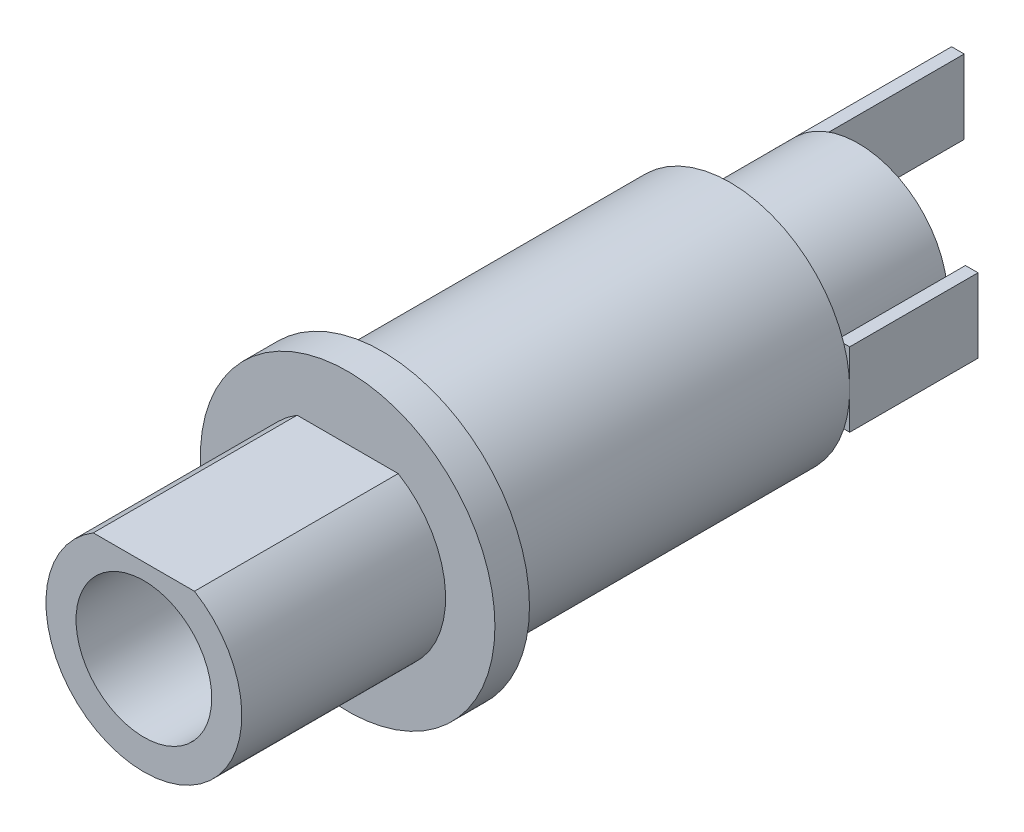
SolidWorks part; units mm, degrees
ref_plane "Plan de face" through (0, 0, 0) normal (0, 0, 1) x (1, 0, 0)
ref_plane "Plan de dessus" through (0, 0, 0) normal (0, 1, 0) x (1, 0, 0)
ref_plane "Plan de droite" through (0, 0, 0) normal (1, 0, 0) x (0, 0, -1)
sketch "Esquisse1" plane through (0, 0, 0) normal (0, 0, 1) x (1, 0, 0)
  circle A0 centre (0, 0) radius 5.97
  dimension "D1" = 11.94
extrude "Boss.-Extru.1" add sketch "Esquisse1" along normal blind 1.4
sketch "Esquisse2" plane through (0, 0, 0) normal (0, 0, -1) x (-1, 0, 0)
  circle A0 centre (0, 0) radius 4.85
  dimension "D1" = 9.7
extrude "Boss.-Extru.2" add sketch "Esquisse2" along normal blind 14.1
sketch "Esquisse3" plane through (0, 0, 1.4) normal (0, 0, 1) x (1, 0, 0)
  circle A0 centre (0, 0) radius 2.75
  circle A1 centre (0, 0) radius 3.97
  dimension "D1" = 7.94
  dimension "D2" = 5.5
extrude "Boss.-Extru.3" add sketch "Esquisse3" along normal blind 8.26
sketch "Esquisse4" plane through (0, 0, 1.4) normal (0, 0, 1) x (1, 0, 0)
  circle A0 centre (0, 0) radius 1
  dimension "D1" = 2
extrude "Boss.-Extru.4" add sketch "Esquisse4" along normal blind 5
sketch "Esquisse5" plane through (0, 0, 0) normal (1, 0, 0) x (0, 0, -1)
  line L0 (-9.66, 3.97) -> (-9.66, -3.97) construction
  line L1 (-1.4, 3.97) -> (-9.66, 3.97)
  line L2 (-1.4, 3.97) -> (-1.4, 3.4)
  line L3 (-1.4, 3.4) -> (-9.66, 3.4)
  line L4 (-9.66, 3.97) -> (-9.66, 3.4)
  line L5 (-1.4, 3.97) -> (-1.4, -3.97) construction
  dimension "D1" = 0.57
extrude "Enlèv. mat.-Extru.1" cut sketch "Esquisse5" against normal up to next and the other way up to next
sketch "Esquisse6" plane through (0, 0, -14.1) normal (0, 0, -1) x (-1, 0, 0)
  line L1 (-4.85, 1.5) -> (-4.34, 1.5)
  line L2 (-4.85, 1.5) -> (-4.85, -1.5)
  line L3 (-4.85, -1.5) -> (-4.34, -1.5)
  line L4 (-4.34, 1.5) -> (-4.34, -1.5)
  circle A0 centre (0, 0) radius 3.62
  circle A1 centre (0, 0) radius 4.85 construction
  point P7 (-4.34, 0)
  dimension "D1" = 7.24
  dimension "D2" = 0.51
  dimension "D3" = 3
extrude "Boss.-Extru.5" add sketch "Esquisse6" along normal blind 5.2
sketch "Esquisse7" plane through (0, 0, -19.3) normal (0, 0, -1) x (-1, 0, 0)
  line L1 (3.11, 1.5) -> (3.62, 1.5)
  line L2 (3.11, 1.5) -> (3.11, -1.5)
  line L3 (3.11, -1.5) -> (3.62, -1.5)
  line L4 (3.62, 1.5) -> (3.62, -1.5)
  circle A1 centre (0, 0) radius 3.62
  circle A2 centre (0, 0) radius 3.62 construction
  point P5 (3.11, 0)
  dimension "D2" = 0.51
  dimension "D3" = 3
  dimension "D1" = 0
extrude "Boss.-Extru.6" add sketch "Esquisse7" along normal blind 7.4
